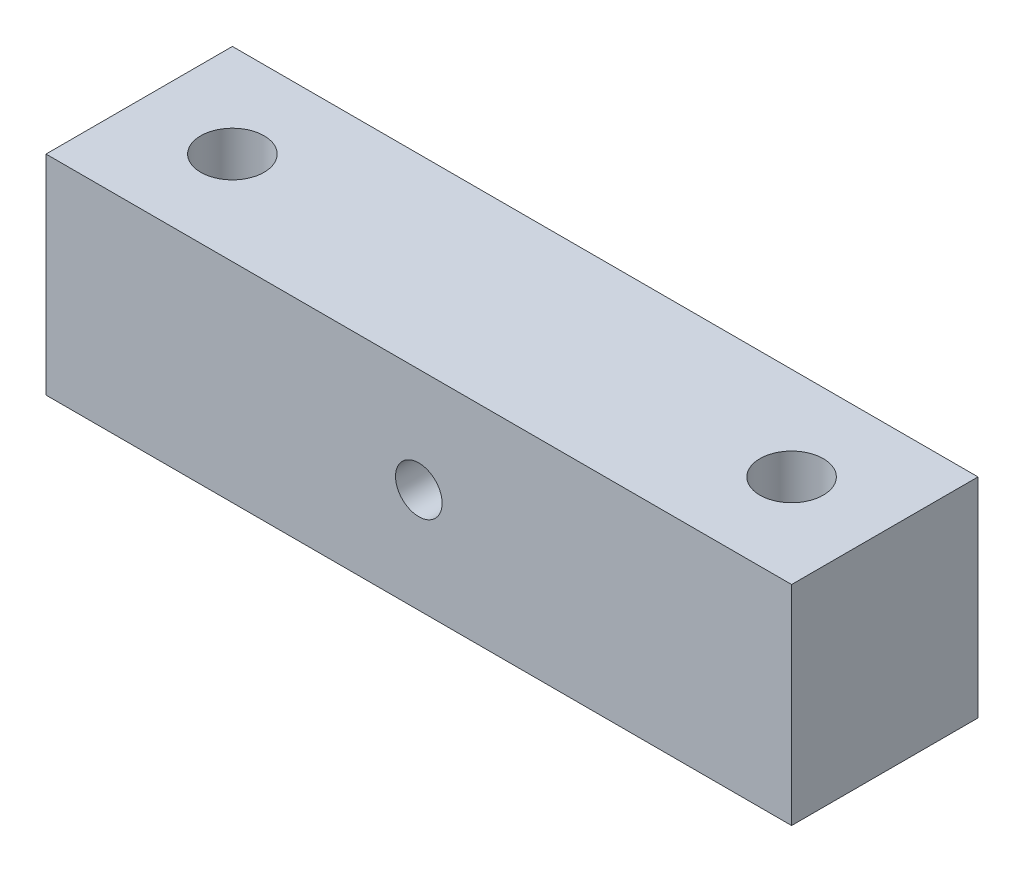
SolidWorks part; units mm, degrees
material "Copper"
ref_plane "Front Plane" through (0, 0, 0) normal (0, 0, 1) x (1, 0, 0)
ref_plane "Top Plane" through (0, 0, 0) normal (0, 1, 0) x (1, 0, 0)
ref_plane "Right Plane" through (0, 0, 0) normal (1, 0, 0) x (0, 0, -1)
sketch "Sketch1" plane through (0, 0, 0) normal (0, 1, 0) x (1, 0, 0)
  line L0 (0, 5) -> (40, 5) construction
  line L1 (0, 0) -> (40, 0)
  line L2 (0, 0) -> (0, 10)
  line L3 (0, 10) -> (40, 10)
  line L4 (40, 0) -> (40, 10)
  line L5 (5, 5) -> (5, 10) construction
  line L6 (35, 10) -> (35, 5) construction
  dimension "D1" = 5
  dimension "D2" = 5
  dimension "D3" = 5
  dimension "D4" = 5
  dimension "D5" = 40
extrude "Boss-Extrude1" add sketch "Sketch1" along normal blind 11.2
sketch "Sketch2" plane through (0, 11.2, 0) normal (0, 1, 0) x (1, 0, 0)
  point P0 (35, 5)
  point P2 (5, 5)
hole_wizard "M3 Clearance Hole1" positions "3DSketch1" profile "Sketch3" hole size "M3" standard "ANSI Metric" end condition through all
sketch3d "3DSketch1"
  point P0 (5, 11.2, -5)
  point P3 (35, 11.2, -5)
sketch "Sketch3" plane through (5, 11.2, -5) normal (1, 0, 0) x (0, 0, 1)
  line L0 (0, 0) -> (0, 11.2)
  line L1 (0, 11.2) -> (1.7, 11.2)
  line L2 (1.7, 11.2) -> (1.7, 0)
  line L5 (1.7, 0) -> (0, 0)
  line L11 (0, -6.35) -> (0, 107.95) construction
  dimension "Thru Hole Dia." = 3.4
  dimension "Thru Hole Depth" = 11.2
sketch "Sketch5" plane through (0, 0, 0) normal (0, 0, 1) x (1, 0, 0)
  line L0 (20, 11.2) -> (20, 0) construction
  line L1 (0, 11.2) -> (40, 11.2) construction
  line L2 (0, 0) -> (40, 0) construction
  point P6 (20, 5.6)
hole_wizard "M3x0.5 Tapped Hole1" positions "3DSketch2" profile "Sketch6" tap size "M3x0.5" standard "ANSI Metric" end condition through all
sketch3d "3DSketch2"
  point P0 (20, 5.6, 0)
sketch "Sketch6" plane through (20, 5.6, 0) normal (1, 0, 0) x (0, -1, 0)
  line L0 (0, 0) -> (0, 10)
  line L1 (0, 10) -> (1.25, 10)
  line L2 (1.25, 10) -> (1.25, 0)
  line L5 (1.25, 0) -> (0, 0)
  line L11 (0, -6.35) -> (0, 107.95) construction
  dimension "Thru Tap Drill Dia." = 2.5
  dimension "Thru Tap Drill Depth" = 10
cosmetic thread "Hole Thread1" parameters "D2"=3
equation "\"D2@Sketch1\"=\"D1@Sketch1\""
equation "\"D3@Sketch1\"=\"D1@Sketch1\""
